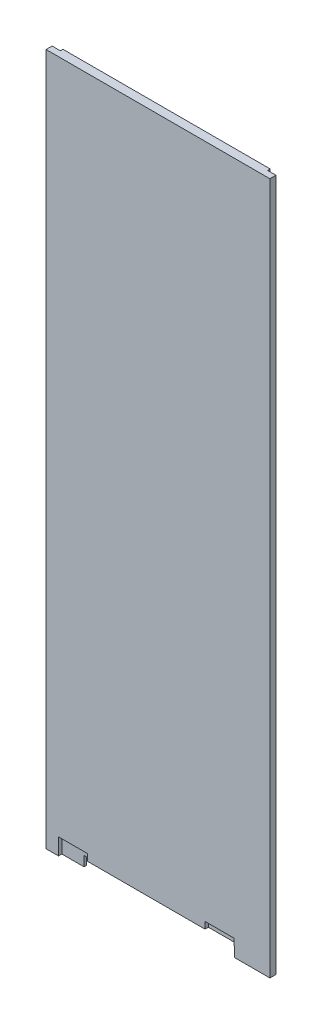
SolidWorks part; units mm, degrees
ref_plane "Front Plane" through (0, 0, 0) normal (0, 0, 1) x (1, 0, 0)
ref_plane "Top Plane" through (0, 0, 0) normal (0, 1, 0) x (1, 0, 0)
ref_plane "Right Plane" through (0, 0, 0) normal (1, 0, 0) x (0, 0, -1)
sketch "Sketch1" plane through (0, 0, 0) normal (0, 0, 1) x (1, 0, 0)
  line L1 (54, 167) -> (-54, 167)
  line L2 (54, 167) -> (54, -167)
  line L3 (54, -167) -> (-54, -167)
  line L4 (-54, 167) -> (-54, -167)
  line L5 (54, 167) -> (-54, -167) construction
  line L6 (54, -167) -> (-54, 167) construction
  point P0 (0, 0)
  dimension "D1" = 334
  dimension "D2" = 108
extrude "Boss-Extrude1" add sketch "Sketch1" along normal blind 2.921
sketch "Sketch2" plane through (0, 0, 2.921) normal (0, 0, 1) x (1, 0, 0)
  line L0 (-54, -167) -> (54, -167) construction
  line L1 (-37.32, -167) -> (36.88, -167)
  line L2 (-37.32, -167) -> (-37.32, -162.2492)
  line L3 (-37.32, -162.2492) -> (36.88, -162.2492)
  line L4 (36.88, -167) -> (36.88, -162.2492)
  line L6 (-54, 167) -> (-54, -167) construction
  dimension "D1" = 16.68
  dimension "D2" = 4.7508
  dimension "D3" = 74.2
extrude "Cut-Extrude1" cut sketch "Sketch2" against normal through all
sketch "Sketch3" plane through (0, -167, 0) normal (0, -1, 0) x (1, 0, 0)
  line L0 (36.88, 2.921) -> (54, 2.921) construction
  line L1 (36.683, 2.921) -> (22.683, 2.921)
  line L2 (36.683, 2.921) -> (36.683, 1.3128)
  line L3 (36.683, 1.3128) -> (22.683, 1.3128)
  line L4 (22.683, 2.921) -> (22.683, 1.3128)
  line L5 (-54, 2.921) -> (-37.32, 2.921) construction
  line L6 (-48, 2.921) -> (-34, 2.921)
  line L7 (-48, 2.921) -> (-48, 1.3128)
  line L8 (-48, 1.3128) -> (-34, 1.3128)
  line L9 (-34, 2.921) -> (-34, 1.3128)
  line L10 (54, 2.921) -> (54, 0) construction
  line L11 (-54, 2.921) -> (-54, 0) construction
  dimension "D1" = 1.6082
  dimension "D2" = 14
  dimension "D3" = 17.317
  dimension "D4" = 6
extrude "Cut-Extrude2" cut sketch "Sketch3" against normal blind 8
sketch "Sketch4" plane through (0, 167, 0) normal (0, 1, 0) x (1, 0, 0)
  line L0 (54, 0) -> (-54, 0) construction
  line L1 (-50, 0) -> (50, 0)
  line L2 (-50, 0) -> (-50, 1.25)
  line L3 (-50, 1.25) -> (50, 1.25)
  line L4 (50, 0) -> (50, 1.25)
  line L5 (0, 0) -> (0, 1.25) construction
  dimension "D1" = 1.25
  dimension "D2" = 100
extrude "Boss-Extrude2" add sketch "Sketch4" against normal blind 2
